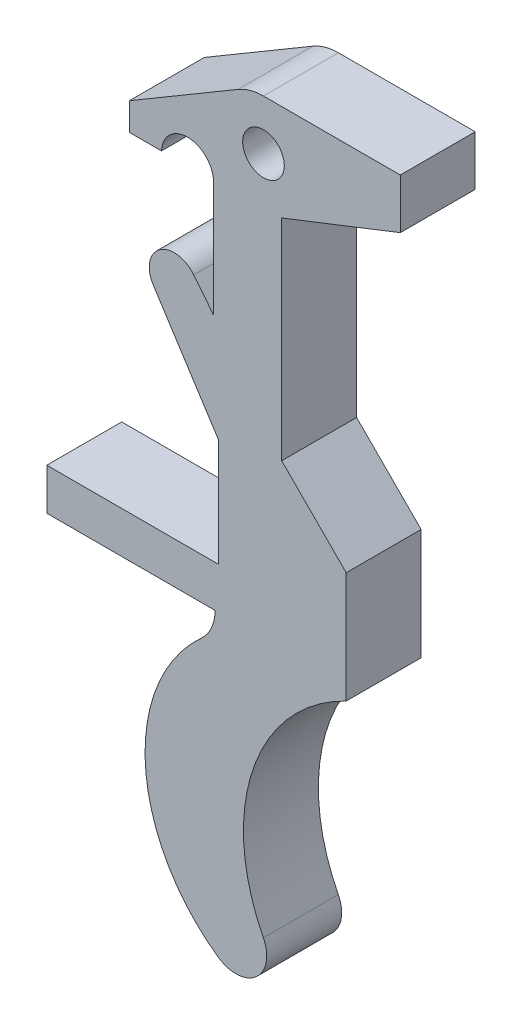
SolidWorks part; units mm, degrees
ref_plane "정면" through (0, 0, 0) normal (0, 0, 1) x (1, 0, 0)
ref_plane "윗면" through (0, 0, 0) normal (0, 1, 0) x (1, 0, 0)
ref_plane "우측면" through (0, 0, 0) normal (1, 0, 0) x (0, 0, -1)
sketch "스케치1" plane through (0, 0, 0) normal (0, 0, 1) x (1, 0, 0)
  line L0 (0, 6) -> (16.4346, 6)
  line L1 (16.4346, 6) -> (16.4346, 0)
  line L2 (16.4346, 0) -> (2.1905, -5.5859)
  line L3 (2.1905, -5.5859) -> (2.1905, -30.8473)
  line L4 (-6, 0) -> (-6, -19.7804)
  line L5 (-16.1111, -2.5414) -> (-3.0496, 5.1672)
  line L8 (-5.4212, -32.4454) -> (-5.4212, -45.4203)
  line L9 (-5.4212, -32.4454) -> (-13.2442, -20.2797)
  line L11 (-26.0295, -45.4203) -> (-10.816, -45.4203)
  line L12 (-5.816, -50.4203) -> (-26.0295, -50.4203)
  line L13 (-26.0295, -50.4203) -> (-26.0295, -45.4203)
  line L14 (-16.1111, -2.5414) -> (-16.1111, -5.8369)
  line L15 (-16.1111, -5.8369) -> (-12.2502, -5.8369)
  line L16 (2.1905, -30.8473) -> (9.9396, -38.6225)
  line L17 (9.9396, -38.6225) -> (9.9396, -51.9748)
  line L19 (-8.3707, -16.7925) -> (-6, -19.7804)
  line L20 (-10.816, -45.4203) -> (-5.4212, -45.4203)
  circle A0 centre (0, 0) radius 2.5
  circle A1 centre (0, 0) radius 6
  arc A2 (-12.2502, -5.8369) -> (-6, -5.8339) centre (-9.125, -5.9635) cw
  arc A3 (9.9396, -51.9748) -> (-0.0131, -81.5804) centre (19.4294, -71.6408) ccw
  arc A4 (-7.4562, -54.1233) -> (-5.4428, -86.3022) centre (6.4116, -69.408) ccw
  arc A5 (-5.4428, -86.3022) -> (-0.0131, -81.5804) centre (-3.3136, -83.2678) ccw
  arc A6 (-5.816, -50.4203) -> (-7.4562, -54.1233) centre (-10.816, -50.4203) cw
  arc A7 (-12.4648, -16.2161) -> (-8.3707, -16.7925) centre (-10.7209, -18.6571) cw
  arc A8 (-13.2442, -20.2797) -> (-12.4648, -16.2161) centre (-10.7209, -18.6571) cw
  dimension "D1" = 5
  dimension "D2" = 12
  dimension "D3" = 5
  dimension "D4" = 3
extrude "보스-돌출1" add sketch "스케치1" along normal blind 9
